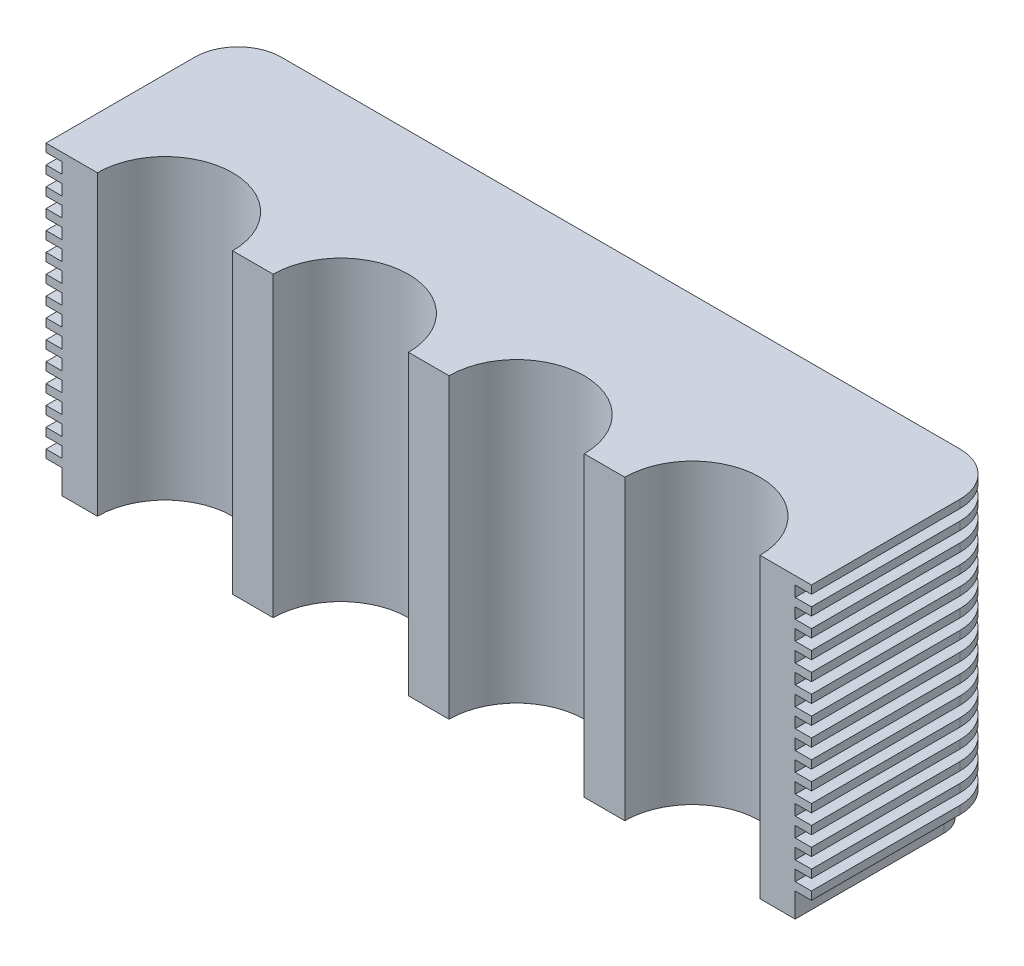
SolidWorks part; units mm, degrees
ref_plane "Front Plane" through (0, 0, 0) normal (0, 0, 1) x (1, 0, 0)
ref_plane "Top Plane" through (0, 0, 0) normal (0, 1, 0) x (1, 0, 0)
ref_plane "Right Plane" through (0, 0, 0) normal (1, 0, 0) x (0, 0, -1)
sketch "Sketch1" plane through (0, 0, 0) normal (0, 1, 0) x (1, 0, 0)
  line L0 (135.5, 0) -> (135.5, 65) construction
  line L1 (0, 0) -> (13, 0)
  line L2 (0, 0) -> (0, 55)
  line L3 (10, 65) -> (261, 65)
  line L4 (271, 0) -> (271, 55)
  line L5 (20.2274, 4.8516) -> (271, 65) construction
  line L6 (0, 0) -> (13, 0) construction
  line L7 (271, 0) -> (0, 65) construction
  line L8 (258, 0) -> (271, 0)
  line L9 (193, 0) -> (208, 0)
  line L10 (63, 0) -> (82.7999, 0) construction
  line L11 (63, 0) -> (78, 0)
  line L12 (128, 0) -> (143, 0)
  arc A0 (261, 65) -> (271, 55) centre (261, 55) cw
  arc A1 (0, 55) -> (10, 65) centre (10, 55) cw
  arc A2 (258, 0) -> (208, 0) centre (233, 0) ccw
  arc A3 (193, 0) -> (143, 0) centre (168, 0) ccw
  arc A4 (13, 0) -> (63, 0) centre (38, 0) cw
  arc A5 (78, 0) -> (128, 0) centre (103, 0) cw
  dimension "D1" = 10
  dimension "D4" = 50
  dimension "D7" = 25
  dimension "D8" = 25
  dimension "D2" = 271
  dimension "D3" = 65
  dimension "D5" = 13
  dimension "D6" = 15
  dimension "D9" = 15
extrude "Boss-Extrude1" add sketch "Sketch1" along normal blind 110
sketch "Sketch2" plane through (0, 0, 0) normal (0, 1, 0) x (1, 0, 0)
  line L8 (0, 55) -> (0, 0)
  line L9 (0, 0) -> (13, 0)
  line L10 (63, 0) -> (78, 0)
  line L11 (128, 0) -> (143, 0)
  line L12 (193, 0) -> (208, 0)
  line L13 (258, 0) -> (271, 0)
  line L14 (271, 0) -> (271, 55)
  line L15 (261, 65) -> (10, 65)
  line L16 (0, 55) -> (0, 0)
  line L17 (0, 0) -> (13, 0)
  line L18 (63, 0) -> (78, 0)
  line L19 (128, 0) -> (143, 0)
  line L20 (193, 0) -> (208, 0)
  line L21 (258, 0) -> (271, 0)
  line L22 (271, 0) -> (271, 55)
  line L23 (261, 65) -> (10, 65)
  arc A6 (63, 0) -> (13, 0) centre (38, 0) ccw
  arc A7 (128, 0) -> (78, 0) centre (103, 0) ccw
  arc A8 (193, 0) -> (143, 0) centre (168, 0) ccw
  arc A9 (258, 0) -> (208, 0) centre (233, 0) ccw
  arc A10 (271, 55) -> (261, 65) centre (261, 55) ccw
  arc A11 (10, 65) -> (0, 55) centre (10, 55) ccw
  arc A12 (63, 0) -> (13, 0) centre (38, 0) ccw
  arc A13 (128, 0) -> (78, 0) centre (103, 0) ccw
  arc A14 (193, 0) -> (143, 0) centre (168, 0) ccw
  arc A15 (258, 0) -> (208, 0) centre (233, 0) ccw
  arc A16 (271, 55) -> (261, 65) centre (261, 55) ccw
  arc A17 (10, 65) -> (0, 55) centre (10, 55) ccw
  dimension "D1" = 0
sketch "Sketch3" plane through (0, 110, 0) normal (0, 1, 0) x (1, 0, 0)
  line L0 (277, 0) -> (277, 55)
  line L1 (261, 71) -> (10, 71)
  line L2 (-6, 55) -> (-6, 0)
  line L3 (271, 0) -> (277, 0)
  line L4 (0, 0) -> (-6, 0)
  line L8 (193, 0) -> (208, 0)
  line L9 (128, 0) -> (143, 0)
  line L10 (63, 0) -> (78, 0)
  line L11 (0, 0) -> (13, 0)
  line L12 (0, 55) -> (0, 0)
  line L13 (261, 65) -> (10, 65)
  line L14 (271, 0) -> (271, 55)
  line L15 (258, 0) -> (271, 0)
  line L20 (0, 55) -> (0, 0)
  line L21 (261, 65) -> (10, 65)
  line L22 (271, 0) -> (271, 55)
  arc A0 (277, 55) -> (261, 71) centre (261, 55) ccw
  arc A1 (10, 71) -> (-6, 55) centre (10, 55) ccw
  arc A6 (193, 0) -> (143, 0) centre (168, 0) ccw
  arc A7 (128, 0) -> (78, 0) centre (103, 0) ccw
  arc A8 (63, 0) -> (13, 0) centre (38, 0) ccw
  arc A9 (10, 65) -> (0, 55) centre (10, 55) ccw
  arc A10 (271, 55) -> (261, 65) centre (261, 55) ccw
  arc A11 (258, 0) -> (208, 0) centre (233, 0) ccw
  arc A15 (10, 65) -> (0, 55) centre (10, 55) ccw
  arc A16 (271, 55) -> (261, 65) centre (261, 55) ccw
  dimension "D1" = 0
  dimension "D2" = 6
extrude "Boss-Extrude2" add sketch "Sketch3" against normal blind 3
pattern_linear "LPattern1" count 15 spacing 7 along (0, -1, 0) of "Boss-Extrude2"
